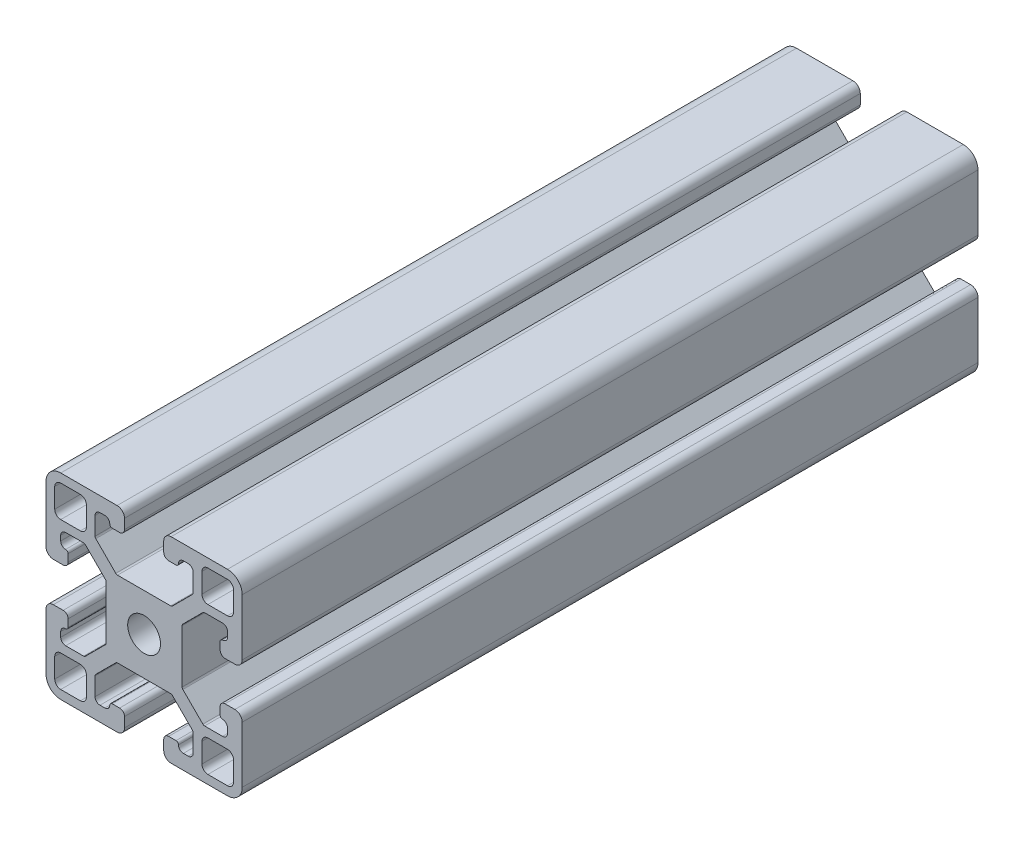
SolidWorks part; units mm, degrees
ref_plane "Front Plane" through (0, 0, 0) normal (0, 0, 1) x (1, 0, 0)
ref_plane "Top Plane" through (0, 0, 0) normal (0, 1, 0) x (1, 0, 0)
ref_plane "Right Plane" through (0, 0, 0) normal (1, 0, 0) x (0, 0, -1)
sketch "Sketch1" plane through (0, 0, 0) normal (0, 0, 1) x (1, 0, 0)
  line B0 (-17, 11.78) -> (-13, 11.78)
  arc B1 (-13, 11.78) -> (-11.78, 13) centre (-13, 13) ccw
  line B2 (-11.78, 13) -> (-11.78, 17)
  arc B3 (-11.78, 17) -> (-13, 18.22) centre (-13, 17) ccw
  line B4 (-13, 18.22) -> (-17, 18.22)
  arc B5 (-17, 18.22) -> (-18.22, 17) centre (-17, 17) ccw
  line B6 (-18.22, 17) -> (-18.22, 13)
  arc B7 (-18.22, 13) -> (-17, 11.78) centre (-17, 13) ccw
  line B8 (-18.22, -13) -> (-18.22, -17)
  arc B9 (-18.22, -17) -> (-17, -18.22) centre (-17, -17) ccw
  line B10 (-17, -18.22) -> (-13, -18.22)
  arc B11 (-13, -18.22) -> (-11.78, -17) centre (-13, -17) ccw
  line B12 (-11.78, -17) -> (-11.78, -13)
  arc B13 (-11.78, -13) -> (-13, -11.78) centre (-13, -13) ccw
  line B14 (-13, -11.78) -> (-17, -11.78)
  arc B15 (-17, -11.78) -> (-18.22, -13) centre (-17, -13) ccw
  line B16 (13, -18.22) -> (17, -18.22)
  arc B17 (17, -18.22) -> (18.22, -17) centre (17, -17) ccw
  line B18 (18.22, -17) -> (18.22, -13)
  arc B19 (18.22, -13) -> (17, -11.78) centre (17, -13) ccw
  line B20 (17, -11.78) -> (13, -11.78)
  arc B21 (13, -11.78) -> (11.78, -13) centre (13, -13) ccw
  line B22 (11.78, -13) -> (11.78, -17)
  arc B23 (11.78, -17) -> (13, -18.22) centre (13, -17) ccw
  line B24 (18.22, 13) -> (18.22, 17)
  arc B25 (18.22, 17) -> (17, 18.22) centre (17, 17) ccw
  line B26 (17, 18.22) -> (13, 18.22)
  arc B27 (13, 18.22) -> (11.78, 17) centre (13, 17) ccw
  line B28 (11.78, 17) -> (11.78, 13)
  arc B29 (11.78, 13) -> (13, 11.78) centre (13, 13) ccw
  line B30 (13, 11.78) -> (17, 11.78)
  arc B31 (17, 11.78) -> (18.22, 13) centre (17, 13) ccw
  line B32 (-9.8536, -11.9786) -> (-5.7714, -7.8964)
  arc B33 (-5.4179, -7.75) -> (-5.7714, -7.8964) centre (-5.4179, -8.25) ccw
  line B34 (-5.4179, -7.75) -> (5.4179, -7.75)
  arc B35 (5.7714, -7.8964) -> (5.4179, -7.75) centre (5.4179, -8.25) ccw
  line B36 (5.7714, -7.8964) -> (9.8536, -11.9786)
  arc B37 (10, -12.3321) -> (9.8536, -11.9786) centre (9.5, -12.3321) ccw
  line B38 (10, -12.3321) -> (10, -16)
  arc B39 (9, -17) -> (10, -16) centre (9, -16) ccw
  line B40 (9, -17) -> (8, -17)
  arc B41 (7, -16) -> (8, -17) centre (8, -16) ccw
  arc B42 (7, -16) -> (6.5, -15.5) centre (6.5, -16) ccw
  line B43 (6.5, -15.5) -> (5, -15.5)
  arc B44 (5, -15.5) -> (4, -16.5) centre (5, -16.5) ccw
  line B45 (4, -16.5) -> (4, -18.5)
  arc B46 (4, -18.5) -> (5.5, -20) centre (5.5, -18.5) ccw
  line B47 (5.5, -20) -> (17, -20)
  arc B48 (17, -20) -> (20, -17) centre (17, -17) ccw
  line B49 (20, -17) -> (20, -5.5)
  arc B50 (20, -5.5) -> (18.5, -4) centre (18.5, -5.5) ccw
  line B51 (18.5, -4) -> (16.5, -4)
  arc B52 (16.5, -4) -> (15.5, -5) centre (16.5, -5) ccw
  line B53 (15.5, -5) -> (15.5, -6.5)
  arc B54 (15.5, -6.5) -> (16, -7) centre (16, -6.5) ccw
  arc B55 (17, -8) -> (16, -7) centre (16, -8) ccw
  line B56 (17, -8) -> (17, -9)
  arc B57 (16, -10) -> (17, -9) centre (16, -9) ccw
  line B58 (16, -10) -> (12.3321, -10)
  arc B59 (11.9786, -9.8536) -> (12.3321, -10) centre (12.3321, -9.5) ccw
  line B60 (11.9786, -9.8536) -> (7.8964, -5.7714)
  arc B61 (7.75, -5.4179) -> (7.8964, -5.7714) centre (8.25, -5.4179) ccw
  line B62 (7.75, -5.4179) -> (7.75, 5.4179)
  arc B63 (7.8964, 5.7714) -> (7.75, 5.4179) centre (8.25, 5.4179) ccw
  line B64 (7.8964, 5.7714) -> (11.9786, 9.8536)
  arc B65 (12.3321, 10) -> (11.9786, 9.8536) centre (12.3321, 9.5) ccw
  line B66 (12.3321, 10) -> (16, 10)
  arc B67 (17, 9) -> (16, 10) centre (16, 9) ccw
  line B68 (17, 9) -> (17, 8)
  arc B69 (16, 7) -> (17, 8) centre (16, 8) ccw
  arc B70 (16, 7) -> (15.5, 6.5) centre (16, 6.5) ccw
  line B71 (15.5, 6.5) -> (15.5, 5)
  arc B72 (15.5, 5) -> (16.5, 4) centre (16.5, 5) ccw
  line B73 (16.5, 4) -> (18.5, 4)
  arc B74 (18.5, 4) -> (20, 5.5) centre (18.5, 5.5) ccw
  line B75 (20, 5.5) -> (20, 17)
  arc B76 (20, 17) -> (17, 20) centre (17, 17) ccw
  line B77 (17, 20) -> (5.5, 20)
  arc B78 (5.5, 20) -> (4, 18.5) centre (5.5, 18.5) ccw
  line B79 (4, 18.5) -> (4, 16.5)
  arc B80 (4, 16.5) -> (5, 15.5) centre (5, 16.5) ccw
  line B81 (5, 15.5) -> (6.5, 15.5)
  arc B82 (6.5, 15.5) -> (7, 16) centre (6.5, 16) ccw
  arc B83 (8, 17) -> (7, 16) centre (8, 16) ccw
  line B84 (8, 17) -> (9, 17)
  arc B85 (10, 16) -> (9, 17) centre (9, 16) ccw
  line B86 (10, 16) -> (10, 12.3321)
  arc B87 (9.8536, 11.9786) -> (10, 12.3321) centre (9.5, 12.3321) ccw
  line B88 (9.8536, 11.9786) -> (5.7714, 7.8964)
  arc B89 (5.4179, 7.75) -> (5.7714, 7.8964) centre (5.4179, 8.25) ccw
  line B90 (5.4179, 7.75) -> (-5.4179, 7.75)
  arc B91 (-5.7714, 7.8964) -> (-5.4179, 7.75) centre (-5.4179, 8.25) ccw
  line B92 (-5.7714, 7.8964) -> (-9.8536, 11.9786)
  arc B93 (-10, 12.3321) -> (-9.8536, 11.9786) centre (-9.5, 12.3321) ccw
  line B94 (-10, 12.3321) -> (-10, 16)
  arc B95 (-9, 17) -> (-10, 16) centre (-9, 16) ccw
  line B96 (-9, 17) -> (-8, 17)
  arc B97 (-7, 16) -> (-8, 17) centre (-8, 16) ccw
  arc B98 (-7, 16) -> (-6.5, 15.5) centre (-6.5, 16) ccw
  line B99 (-6.5, 15.5) -> (-5, 15.5)
  arc B100 (-5, 15.5) -> (-4, 16.5) centre (-5, 16.5) ccw
  line B101 (-4, 16.5) -> (-4, 18.5)
  arc B102 (-4, 18.5) -> (-5.5, 20) centre (-5.5, 18.5) ccw
  line B103 (-5.5, 20) -> (-17, 20)
  arc B104 (-17, 20) -> (-20, 17) centre (-17, 17) ccw
  line B105 (-20, 17) -> (-20, 5.5)
  arc B106 (-20, 5.5) -> (-18.5, 4) centre (-18.5, 5.5) ccw
  line B107 (-18.5, 4) -> (-16.5, 4)
  arc B108 (-16.5, 4) -> (-15.5, 5) centre (-16.5, 5) ccw
  line B109 (-15.5, 5) -> (-15.5, 6.5)
  arc B110 (-15.5, 6.5) -> (-16, 7) centre (-16, 6.5) ccw
  arc B111 (-17, 8) -> (-16, 7) centre (-16, 8) ccw
  line B112 (-17, 8) -> (-17, 9)
  arc B113 (-16, 10) -> (-17, 9) centre (-16, 9) ccw
  line B114 (-16, 10) -> (-12.3321, 10)
  arc B115 (-11.9786, 9.8536) -> (-12.3321, 10) centre (-12.3321, 9.5) ccw
  line B116 (-11.9786, 9.8536) -> (-7.8964, 5.7714)
  arc B117 (-7.75, 5.4179) -> (-7.8964, 5.7714) centre (-8.25, 5.4179) ccw
  line B118 (-7.75, 5.4179) -> (-7.75, -5.4179)
  arc B119 (-7.8964, -5.7714) -> (-7.75, -5.4179) centre (-8.25, -5.4179) ccw
  line B120 (-7.8964, -5.7714) -> (-11.9786, -9.8536)
  arc B121 (-12.3321, -10) -> (-11.9786, -9.8536) centre (-12.3321, -9.5) ccw
  line B122 (-12.3321, -10) -> (-16, -10)
  arc B123 (-17, -9) -> (-16, -10) centre (-16, -9) ccw
  line B124 (-17, -9) -> (-17, -8)
  arc B125 (-16, -7) -> (-17, -8) centre (-16, -8) ccw
  arc B126 (-16, -7) -> (-15.5, -6.5) centre (-16, -6.5) ccw
  line B127 (-15.5, -6.5) -> (-15.5, -5)
  arc B128 (-15.5, -5) -> (-16.5, -4) centre (-16.5, -5) ccw
  line B129 (-16.5, -4) -> (-18.5, -4)
  arc B130 (-18.5, -4) -> (-20, -5.5) centre (-18.5, -5.5) ccw
  line B131 (-20, -5.5) -> (-20, -17)
  arc B132 (-20, -17) -> (-17, -20) centre (-17, -17) ccw
  line B133 (-17, -20) -> (-5.5, -20)
  arc B134 (-5.5, -20) -> (-4, -18.5) centre (-5.5, -18.5) ccw
  line B135 (-4, -18.5) -> (-4, -16.5)
  arc B136 (-4, -16.5) -> (-5, -15.5) centre (-5, -16.5) ccw
  line B137 (-5, -15.5) -> (-6.5, -15.5)
  arc B138 (-6.5, -15.5) -> (-7, -16) centre (-6.5, -16) ccw
  arc B139 (-8, -17) -> (-7, -16) centre (-8, -16) ccw
  line B140 (-8, -17) -> (-9, -17)
  arc B141 (-10, -16) -> (-9, -17) centre (-9, -16) ccw
  line B142 (-10, -16) -> (-10, -12.3321)
  arc B143 (-9.8536, -11.9786) -> (-10, -12.3321) centre (-9.5, -12.3321) ccw
  circle B144 centre (0, 0) radius 3.35
sketch_block_instance "S8-4040 - S-1"
sketch_block "S8-4040 - S"
extrude "Boss-Extrude1" add sketch "Sketch1" along normal blind 150
